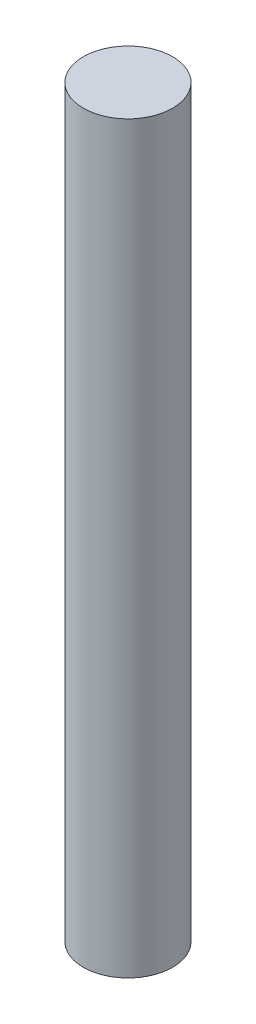
SolidWorks part; units mm, degrees
ref_plane "Front Plane" through (0, 0, 0) normal (0, 0, 1) x (1, 0, 0)
ref_plane "Top Plane" through (0, 0, 0) normal (0, 1, 0) x (1, 0, 0)
ref_plane "Right Plane" through (0, 0, 0) normal (1, 0, 0) x (0, 0, -1)
sketch "Sketch1" plane through (0, 0, 0) normal (0, 1, 0) x (1, 0, 0)
  circle A0 centre (0, 0) radius 3
extrude "Boss-Extrude1" add sketch "Sketch1" along normal blind 50
